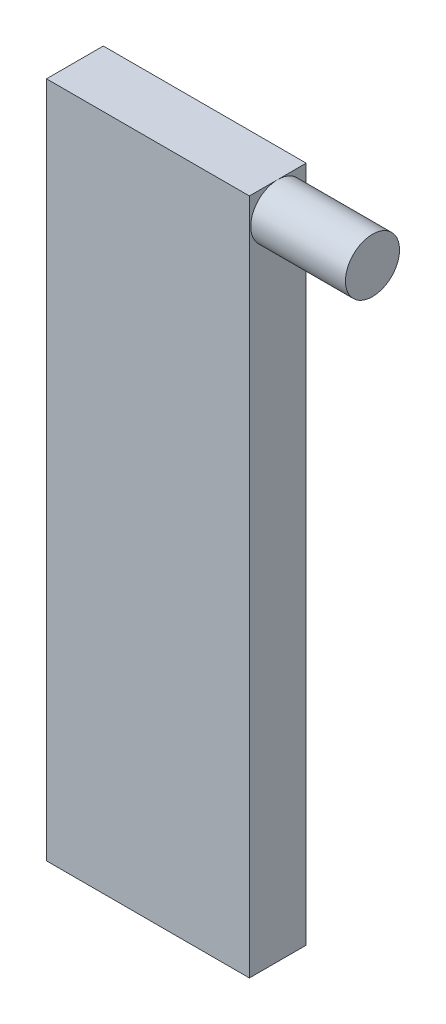
SolidWorks part; units mm, degrees
ref_plane "Front Plane" through (0, 0, 0) normal (0, 0, 1) x (1, 0, 0)
ref_plane "Top Plane" through (0, 0, 0) normal (0, 1, 0) x (1, 0, 0)
ref_plane "Right Plane" through (0, 0, 0) normal (1, 0, 0) x (0, 0, -1)
sketch "Sketch1" plane through (0, 0, 0) normal (0, 0, 1) x (1, 0, 0)
  line L5 (-65.3083, -126.3606) -> (-50.3083, -126.3606)
  line L6 (-65.3083, -126.3606) -> (-65.3083, -176.4306)
  line L7 (-65.3083, -176.4306) -> (-50.3083, -176.4306)
  line L8 (-50.3083, -126.3606) -> (-50.3083, -176.4306)
  dimension "D1" = 15
  dimension "D2" = 50.07
extrude "Boss-Extrude1" add sketch "Sketch1" along normal blind 4.2
sketch "Sketch2" plane through (-50.3083, 0, 0) normal (1, 0, 0) x (0, 0, -1)
  line L0 (0, -176.4306) -> (0, -126.3606) construction
  line L1 (-4.2, -126.3606) -> (0, -126.3606) construction
  circle A0 centre (-2.1, -128.3606) radius 2
  point P4 (0, 0)
  dimension "D1" = 4
  dimension "D2" = 2.1
  dimension "D3" = 2
extrude "Boss-Extrude2" add sketch "Sketch2" along normal blind 7
